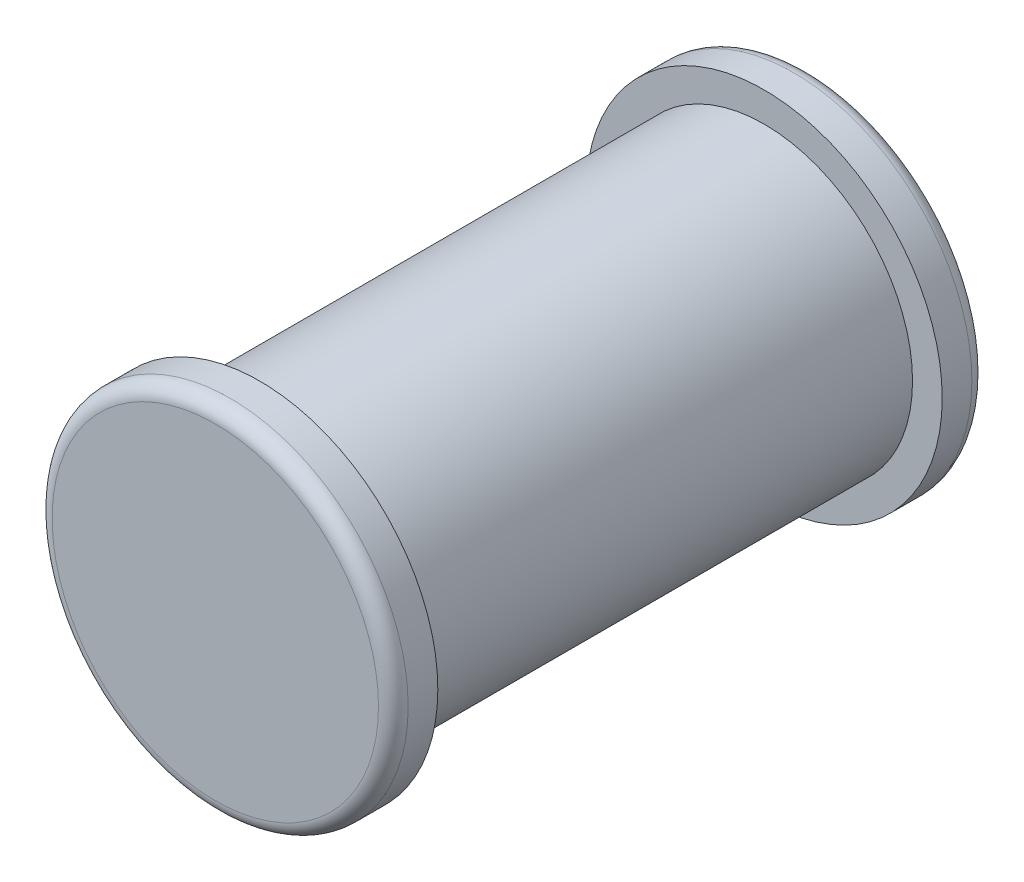
SolidWorks part; units mm, degrees
ref_plane "前视基准面" through (0, 0, 0) normal (0, 0, 1) x (1, 0, 0)
ref_plane "上视基准面" through (0, 0, 0) normal (0, 1, 0) x (1, 0, 0)
ref_plane "右视基准面" through (0, 0, 0) normal (1, 0, 0) x (0, 0, -1)
sketch "草图1" plane through (0, 0, 0) normal (0, 0, 1) x (1, 0, 0)
  circle A0 centre (0, 0) radius 10
extrude "凸台-拉伸1" add sketch "草图1" along normal blind 40
sketch "草图3" plane through (0, 0, 40) normal (0, 0, 1) x (1, 0, 0)
  circle A0 centre (0, 0) radius 10
extrude "拉伸-薄壁1" add sketch "草图3" against normal blind 3 thin
sketch "草图4" plane through (0, 0, 0) normal (0, 0, -1) x (-1, 0, 0)
  circle A0 centre (0, 0) radius 10
extrude "拉伸-薄壁2" add sketch "草图4" against normal blind 3 thin
fillet "圆角4" radius 1 2 edges at (12, 0, 40) (-12, 0, 0)
